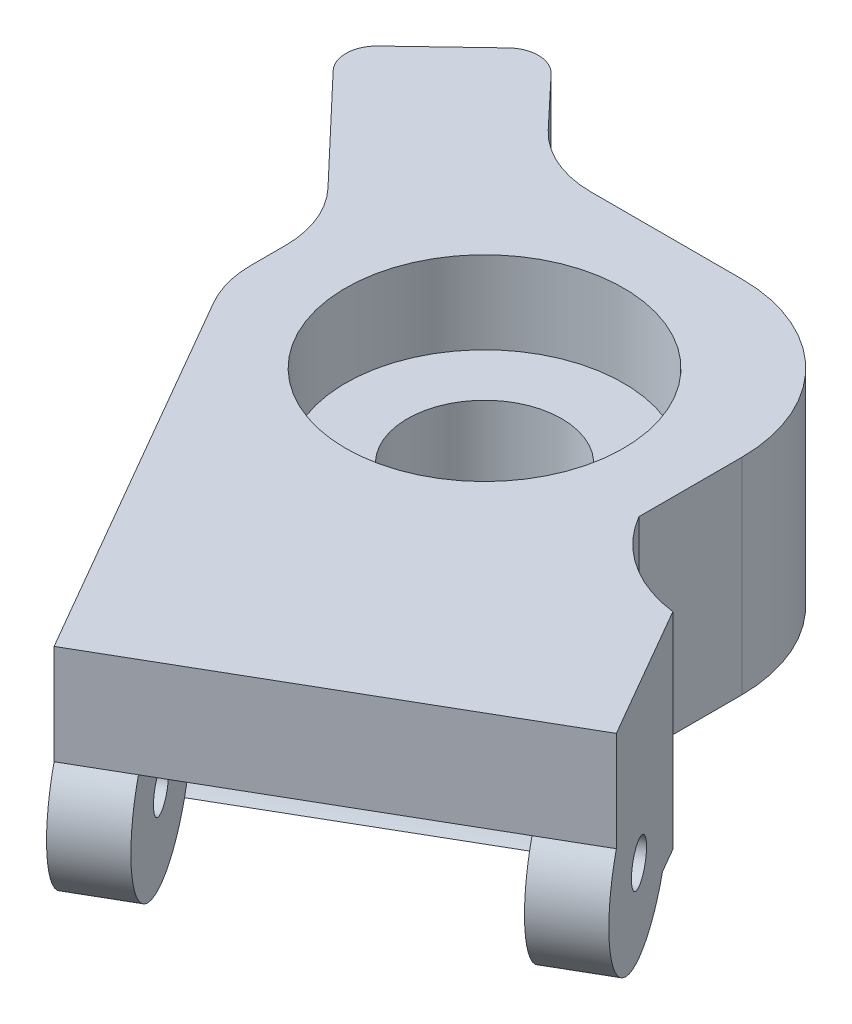
SolidWorks part; units mm, degrees
ref_plane "Front Plane" through (0, 0, 0) normal (0, 0, 1) x (1, 0, 0)
ref_plane "Top Plane" through (0, 0, 0) normal (0, 1, 0) x (1, 0, 0)
ref_plane "Right Plane" through (0, 0, 0) normal (1, 0, 0) x (0, 0, -1)
sketch "Sketch1" plane through (0, 0, 0) normal (0, 1, 0) x (1, 0, 0)
  line L0 (0, -4) -> (0, -3) construction
  line L1 (-20, 20) -> (20, 20) construction
  line L2 (-20, 20) -> (-20, 14) construction
  line L3 (-20, -20) -> (20, -20) construction
  line L4 (20, 20) -> (20, -20) construction
  line L5 (-20, 20) -> (20, -20) construction
  line L6 (-20, -20) -> (20, 20) construction
  line L11 (0, 0) -> (35.9445, -62.2576) construction
  line L12 (-20, -20) -> (20, -20) construction
  line L13 (-2.6458, -3) -> (2.6458, -3) construction
  line L14 (-20, -20) -> (-20, -22) construction
  line L15 (-20, -22) -> (20, -22) construction
  line L16 (20, -20) -> (20, -22) construction
  line L17 (2.5, -44.3301) -> (37.141, -24.3301)
  line L18 (37.141, -24.3301) -> (29.641, -11.3397)
  line L19 (2.5, -44.3301) -> (-20, -5.359)
  line L20 (-20, 20) -> (-20, 14) construction
  line L21 (20, 5) -> (20, -5)
  line L22 (-14, 20) -> (-23.5932, 30.1966)
  line L25 (-20, 4.641) -> (-20, -5.359)
  line L26 (-14, 20) -> (5, 20)
  line L30 (-20, 4.641) -> (-20, -20) construction
  line L31 (-20, 4.641) -> (-20, -5.359) construction
  line L32 (-34.4664, 19.8635) -> (-23.5932, 30.1966)
  line L33 (-34.4664, 19.8635) -> (-20, 4.641)
  circle A0 centre (0, 0) radius 4 construction
  arc A3 (-2.6458, -3) -> (2.6458, -3) centre (0, 0) cw construction
  arc A4 (20, -5) -> (29.641, -11.3397) centre (31.2212, 1.5639) ccw
  arc A5 (20, 5) -> (5, 20) centre (5, 5) ccw
  circle A6 centre (0, 0) radius 13.5
  point P0 (0, 0)
  point P19 (0, -3)
  point P25 (19.8205, -34.3301)
  dimension "D3" = 8
  dimension "D6" = 14
  dimension "D7" = 21
  dimension "D8" = 1
  dimension "D4" = 15
  dimension "D5" = 15
  dimension "D9" = 10
  dimension "D10" = 25
  dimension "D11" = 20
  dimension "D12" = 20
  dimension "D22" = 13
  dimension "D19" = 27
  dimension "D1" = 40
  dimension "D2" = 40
  dimension "D13" = 42
  dimension "D14" = 30
  dimension "D15" = 40
  dimension "D16" = 45
  dimension "D17" = 6
  dimension "D18" = 6
  dimension "D21" = 15
extrude "Boss-Extrude1" add sketch "Sketch1" along normal blind 8
sketch "Sketch7" plane through (0, 0, 0) normal (0, -1, 0) x (1, 0, 0)
  line L2 (-20, 5.359) -> (2.5, 44.3301) construction
  line L4 (-20, -4.641) -> (-20, 5.359) construction
  line L6 (20, 5) -> (20, -5)
  line L7 (5, -20) -> (-14, -20)
  line L8 (-14, -20) -> (-23.5932, -30.1966)
  line L9 (-23.5932, -30.1966) -> (-34.4664, -19.8635)
  line L10 (-34.4664, -19.8635) -> (-20, -4.641)
  line L11 (-20, 5.359) -> (-20, -4.641)
  line L12 (-20, 5.359) -> (2.5, 44.3301)
  line L14 (-34.4664, -19.8635) -> (-20, -4.641) construction
  line L15 (-23.5932, -30.1966) -> (-34.4664, -19.8635) construction
  line L16 (-14, -20) -> (-23.5932, -30.1966) construction
  line L17 (5, -20) -> (-14, -20) construction
  line L18 (37.141, 24.3301) -> (29.641, 11.3397)
  line L19 (2.5, 44.3301) -> (37.141, 24.3301)
  arc A0 (20, 5) -> (29.641, 11.3397) centre (31.2212, -1.5639) cw
  arc A1 (20, -5) -> (5, -20) centre (5, -5) cw
  circle A5 centre (0, 0) radius 7.5
  arc A6 (5, -20) -> (20, -5) centre (5, -5) ccw construction
  point P40 (-20, 0.359)
  dimension "D1" = 13
  dimension "D2" = 15
extrude "Boss-Extrude3" add sketch "Sketch7" along normal blind 12
sketch "Sketch4" plane through (19.8205, 0, 34.3301) normal (0.5, 0, 0.866) x (0.866, 0, -0.5)
  line L0 (20, -12) -> (-20, -12) construction
  line L1 (-14, -12) -> (14, -12)
  line L2 (-14, -12) -> (-14, -2)
  line L3 (-14, -2) -> (14, -2)
  line L4 (14, -12) -> (14, -2)
  line L5 (20, 8) -> (20, -12) construction
  line L6 (-20, 8) -> (-20, -12) construction
  dimension "D1" = 10
  dimension "D2" = 6
  dimension "D3" = 6
extrude "Cut-Extrude2" cut sketch "Sketch4" against normal blind 12
sketch "Sketch5" plane through (17.3205, 0, -10) normal (0.866, 0, -0.5) x (-0.5, 0, -0.866)
  line L0 (-24.641, -12) -> (-39.641, -12) construction
  line L1 (-39.641, 8) -> (-39.641, -12) construction
  circle A0 centre (-33.641, -7) radius 2
  dimension "D1" = 5
  dimension "D2" = 6
  dimension "D3" = 4
extrude "Cut-Extrude3" cut sketch "Sketch5" against normal blind 100
sketch "Sketch9" plane through (17.3205, 0, -10) normal (0.866, 0, -0.5) x (-0.5, 0, -0.866)
  circle A0 centre (-33.641, -7) radius 8
  circle A1 centre (-33.641, -7) radius 2
  dimension "D1" = 16
  dimension "D2" = 4
extrude "Boss-Extrude4" add sketch "Sketch9" against normal blind 40
fillet "Fillet2" radius 10 3 edges at (-14, -2, -20) (-20, -2, -4.641) (-20, -2, 5.359)
fillet "Fillet3" radius 3 2 edges at (-34.4664, -2, -19.8635) (-23.5932, -2, -30.1966)
ref_plane "Plane1" through (0, 0, 0) normal (0.866, 0, -0.5) x (-0.5, 0, -0.866)
sketch "Sketch11" plane through (0, 0, 0) normal (0.866, 0, -0.5) x (-0.5, 0, -0.866)
  circle A0 centre (-33.641, -7) radius 8
  dimension "D1" = 16
extrude "Cut-Extrude6" cut sketch "Sketch11" against normal mid plane 28
